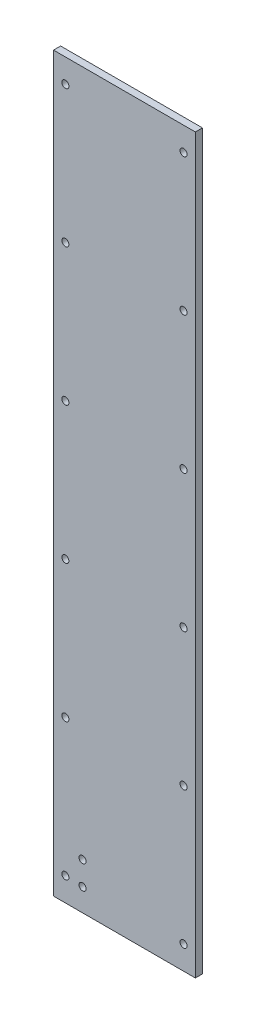
SolidWorks part; units mm, degrees
ref_plane "Plan de face" through (0, 0, 0) normal (0, 0, 1) x (1, 0, 0)
ref_plane "Plan de dessus" through (0, 0, 0) normal (0, 1, 0) x (1, 0, 0)
ref_plane "Plan de droite" through (0, 0, 0) normal (1, 0, 0) x (0, 0, -1)
sketch "Esquisse1" plane through (0, 0, 0) normal (0, 0, 1) x (1, 0, 0)
  line L0 (-30, 0) -> (30, 0) construction
  line L1 (30, -155) -> (-30, -155)
  line L2 (30, -155) -> (30, 155)
  line L3 (30, 155) -> (-30, 155)
  line L4 (-30, -155) -> (-30, 155)
  line L5 (30, -155) -> (-30, 155) construction
  line L6 (30, 155) -> (-30, -155) construction
  line L7 (-30, -155) -> (-20, -155)
  line L8 (-30, -155) -> (-30, -150)
  line L13 (-30, 155) -> (-20, 155)
  line L14 (-30, 155) -> (-30, 150)
  line L15 (-25, -155) -> (-25, 155) construction
  line L16 (0, 155) -> (0, -155) construction
  line L17 (-25, -145) -> (-25, -87) construction
  circle A0 centre (-25, -145) radius 1.5
  circle A1 centre (-25, -87) radius 1.5
  circle A2 centre (-25, -29) radius 1.5
  circle A3 centre (-25, 29) radius 1.5
  circle A4 centre (-25, 87) radius 1.5
  circle A5 centre (-25, 145) radius 1.5
  circle A6 centre (25, -87) radius 1.5
  circle A7 centre (25, -145) radius 1.5
  circle A8 centre (25, -29) radius 1.5
  circle A9 centre (25, 29) radius 1.5
  circle A10 centre (25, 87) radius 1.5
  circle A11 centre (25, 145) radius 1.5
  circle A12 centre (-17.7283, -135.4553) radius 1.5
  circle A14 centre (-17.7283, -145.4553) radius 1.5
  point P0 (0, 0)
  dimension "D5" = 3
  dimension "D3" = 3
  dimension "D4" = 3
  dimension "D1" = 60
  dimension "D2" = 310
  dimension "D7" = 58
  dimension "D8" = 6
extrude "Boss.-Extru.1" add sketch "Esquisse1" along normal blind 3
